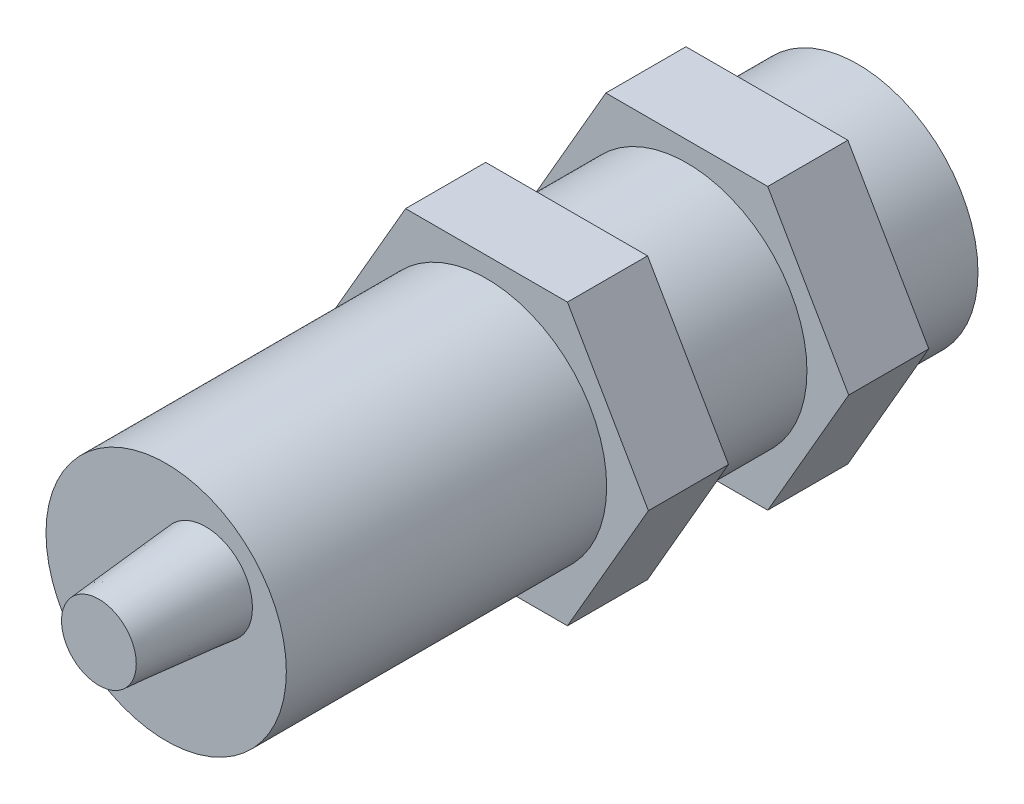
SolidWorks part; units mm, degrees
ref_plane "Ön Düzlem" through (0, 0, 0) normal (0, 0, 1) x (1, 0, 0)
ref_plane "Üst Düzlem" through (0, 0, 0) normal (0, 1, 0) x (1, 0, 0)
ref_plane "Sağ Düzlem" through (0, 0, 0) normal (1, 0, 0) x (0, 0, -1)
sketch "Çizim1" plane through (0, 0, 0) normal (0, 0, 1) x (1, 0, 0)
  circle A0 centre (0, 0) radius 9
  dimension "D1" = 18
extrude "Yükseklik-Ekstrüzyon1" add sketch "Çizim1" along normal blind 51.8
sketch "Çizim2" plane through (0, 0, 51.8) normal (0, 0, 1) x (1, 0, 0)
  circle A0 centre (2.9613, 2.8784) radius 3.5
  dimension "D1" = 7
extrude "Yükseklik-Ekstrüzyon2" add sketch "Çizim2" along normal blind 8 draft 5
ref_plane "Düzlem4" through (0, 0, 6.81) normal (0, 0, -1) x (-1, 0, 0)
sketch "Çizim6" plane through (0, 0, 6.81) normal (0, 0, -1) x (-1, 0, 0)
  line L0 (0.3139, 0) -> (-4.7357, 0) construction
  line L1 (6.0622, 10.5) -> (-6.0622, 10.5)
  line L2 (-6.0622, 10.5) -> (-12.1244, 0)
  line L3 (-12.1244, 0) -> (-6.0622, -10.5)
  line L4 (-6.0622, -10.5) -> (6.0622, -10.5)
  line L5 (6.0622, -10.5) -> (12.1244, 0)
  line L6 (12.1244, 0) -> (6.0622, 10.5)
  circle A0 centre (0, 0) radius 10.5 construction
  dimension "D1" = 21
extrude "Yükseklik-Ekstrüzyon3" add sketch "Çizim6" against normal blind 6
pattern_linear "LPattern1" count 2 spacing 15 along (0, 0, 1) of "Yükseklik-Ekstrüzyon3"
